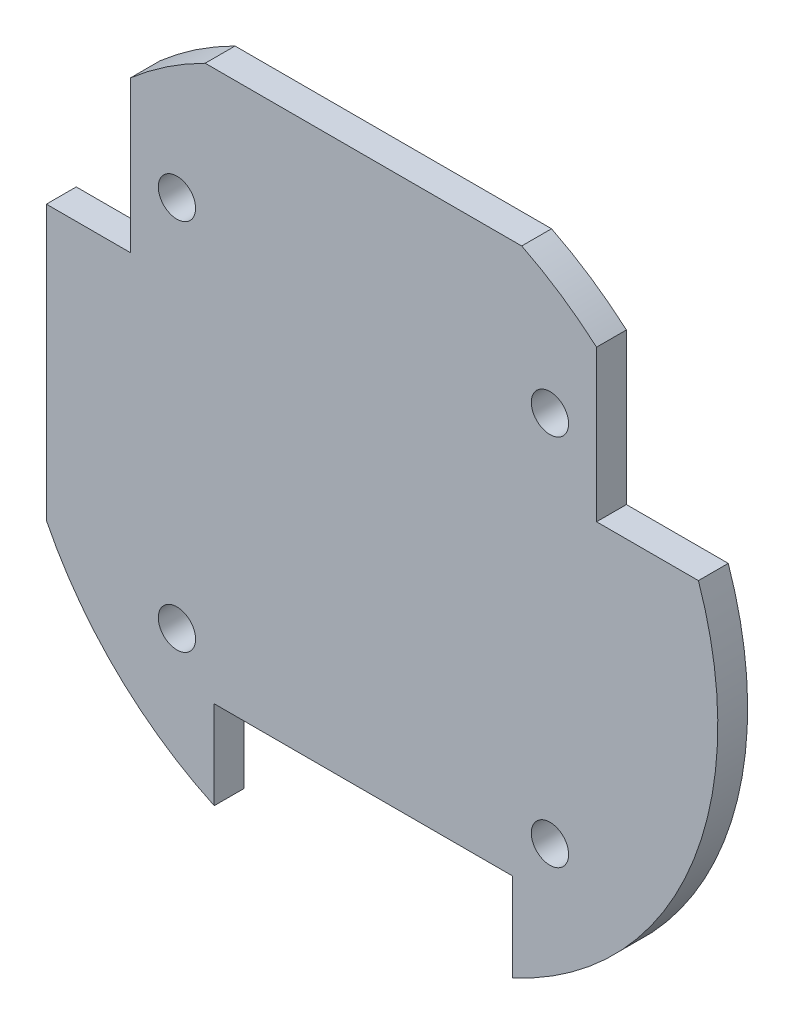
SolidWorks part; units mm, degrees
ref_plane "Front Plane" through (0, 0, 0) normal (0, 0, 1) x (1, 0, 0)
ref_plane "Top Plane" through (0, 0, 0) normal (0, 1, 0) x (1, 0, 0)
ref_plane "Right Plane" through (0, 0, 0) normal (1, 0, 0) x (0, 0, -1)
sketch "Sketch1" plane through (0, 0, 0) normal (0, 0, 1) x (1, 0, 0)
  line L0 (-10, -3.2504) -> (10, -23.2504) construction
  line L1 (10, -3.2504) -> (-10, -23.2504) construction
  circle A1 centre (-10, -3.2504) radius 1
  circle A3 centre (10, -3.2504) radius 1
  circle A5 centre (10, -23.2504) radius 1
  circle A7 centre (-10, -23.2504) radius 1
  circle A8 centre (0, -13.2504) radius 19
  dimension "D1" = 38
extrude "Boss-Extrude1" add sketch "Sketch1" along normal blind 1.6
sketch "Sketch2" plane through (0, 0, 1.6) normal (0, 0, 1) x (1, 0, 0)
  line L0 (-8.4853, 3.7496) -> (8.4853, 3.7496)
  line L1 (8.4853, 3.7496) -> (8.4853, 7.313)
  line L2 (8.4853, 7.313) -> (-8.4853, 7.313)
  line L3 (-8.4853, 7.313) -> (-8.4853, 3.7496)
  line L4 (-17, -4.7651) -> (-17, -21.7357)
  line L5 (-17, -4.7651) -> (-22.1499, -4.7651)
  line L6 (-22.1499, -4.7651) -> (-22.1499, -21.7357)
  line L7 (-22.1499, -21.7357) -> (-17, -21.7357)
  circle A0 centre (0, -13.2504) radius 19 construction
  dimension "D1" = 2
  dimension "D2" = 2
extrude "Cut-Extrude1" cut sketch "Sketch2" against normal blind 1.6
sketch "Sketch3" plane through (0, 0, 0) normal (0, 0, -1) x (-1, 0, 0)
  line L0 (12.5, -5.1504) -> (12.5, -7.0504)
  line L1 (12.5, -7.0504) -> (17, -7.0504)
  line L2 (17, -21.7357) -> (17, -4.7651) construction
  line L4 (12.5, -5.1504) -> (12.5, 1.0587)
  line L5 (12.5, 1.0587) -> (18.9899, 1.0587)
  line L6 (18.9899, 1.0587) -> (17, -7.0504) construction
  line L8 (8.4853, 3.7496) -> (-8.4853, 3.7496) construction
  line L9 (17, -7.0504) -> (24.2182, -7.0504)
  line L10 (24.2182, -7.0504) -> (24.2182, 1.0587)
  line L11 (24.2182, 1.0587) -> (18.9899, 1.0587)
  arc A0 (17, -4.7651) -> (8.4853, 3.7496) centre (0, -13.2504) ccw construction
  dimension "D1" = 4.5
  dimension "D2" = 10.8
extrude "Cut-Extrude2" cut sketch "Sketch3" against normal blind 1.6
mirror "Mirror1" about plane through (0, 0, 0) normal (1, 0, 0) of "Cut-Extrude2"
sketch "Sketch4" plane through (0, 0, 1.6) normal (0, 0, 1) x (1, 0, 0)
  line L0 (0, 3.7496) -> (0, -31.2843) construction
  line L1 (-8.4853, 3.7496) -> (8.4853, 3.7496) construction
  line L3 (-8, -36.8182) -> (8, -36.8182)
  line L4 (-8, -36.8182) -> (-8, -25.7504)
  line L5 (-8, -25.7504) -> (8, -25.7504)
  line L6 (8, -36.8182) -> (8, -25.7504)
  line L7 (-8, -36.8182) -> (8, -25.7504) construction
  line L8 (-8, -25.7504) -> (8, -36.8182) construction
  arc A0 (-17, -21.7357) -> (17.96, -7.0504) centre (0, -13.2504) ccw construction
  dimension "D1" = 16
  dimension "D2" = 12.5
extrude "Cut-Extrude3" cut sketch "Sketch4" against normal blind 1.6
